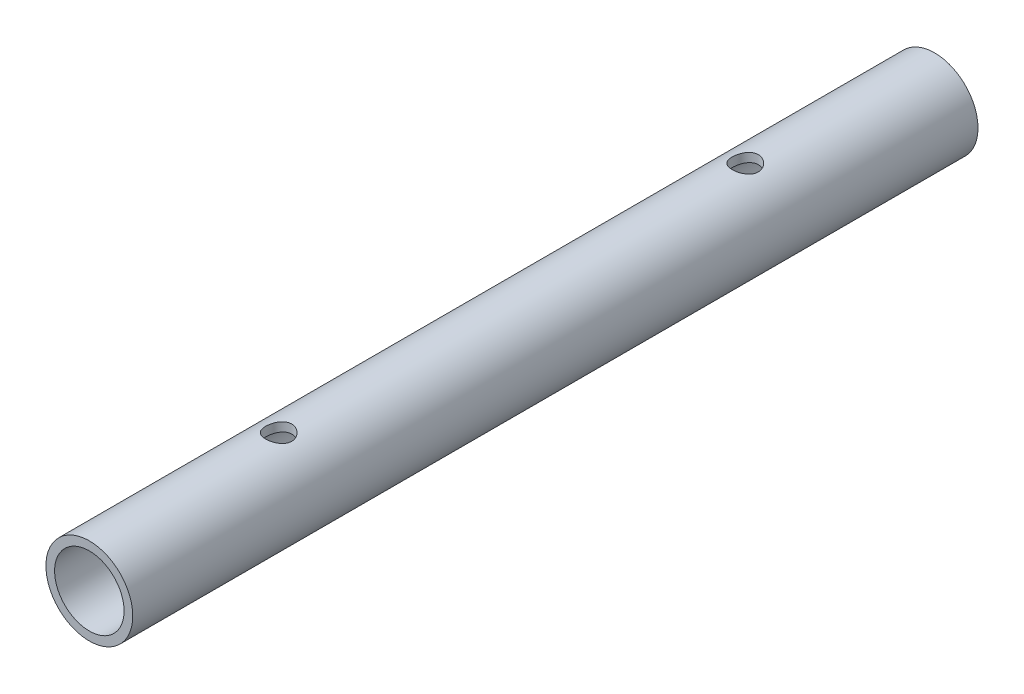
SolidWorks part; units mm, degrees
ref_plane "Plan de face" through (0, 0, 0) normal (0, 0, 1) x (1, 0, 0)
ref_plane "Plan de dessus" through (0, 0, 0) normal (0, 1, 0) x (1, 0, 0)
ref_plane "Plan de droite" through (0, 0, 0) normal (1, 0, 0) x (0, 0, -1)
sketch "Sketch1" plane through (0, 0, 0) normal (0, 0, 1) x (1, 0, 0)
  circle A0 centre (0, 0) radius 5
extrude "Boss-Extrude1" add sketch "Sketch1" along normal blind 97.338
sketch "Sketch2" plane through (0, 0, 97.338) normal (0, 0, 1) x (1, 0, 0)
  circle A0 centre (0, 0) radius 4
extrude "Cut-Extrude1" cut sketch "Sketch2" against normal up to next
sketch "Sketch5" plane through (0, 0, 0) normal (0, 1, 0) x (1, 0, 0)
  circle A0 centre (0, -21.804) radius 1.5
  circle A1 centre (0, -75.534) radius 1.5
  dimension "D1" = 21.804
  dimension "D2" = 75.534
extrude "Cut-Extrude2" cut sketch "Sketch5" against normal through all and the other way through all
